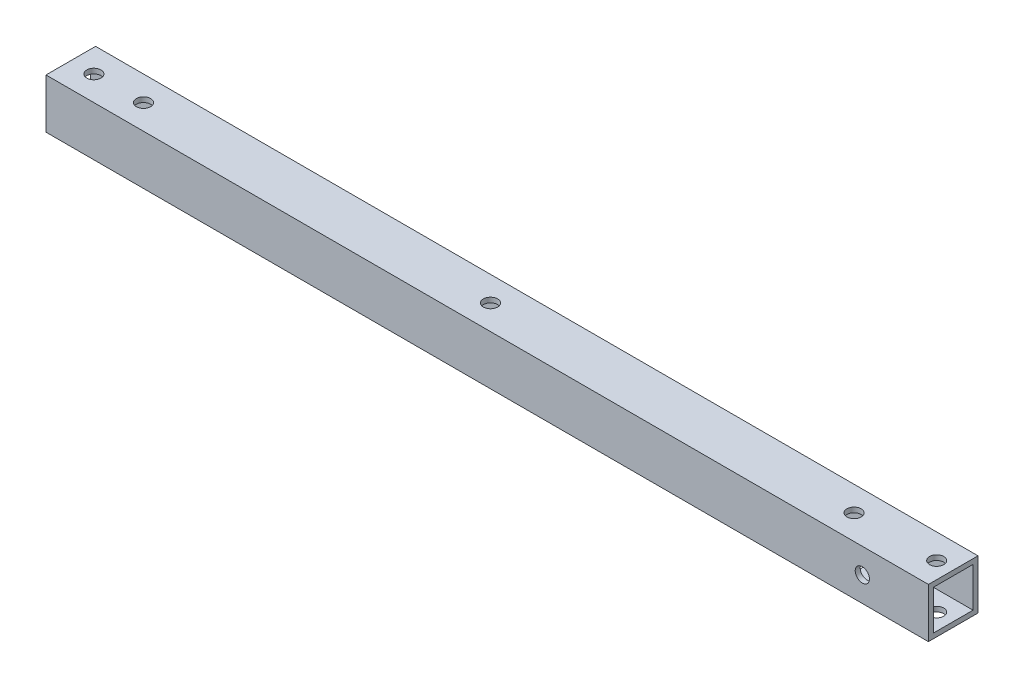
SolidWorks part; units mm, degrees
material "5052-H34"
ref_plane "正面" through (0, 0, 0) normal (0, 0, 1) x (1, 0, 0)
ref_plane "平面" through (0, 0, 0) normal (0, 1, 0) x (1, 0, 0)
ref_plane "右側面" through (0, 0, 0) normal (1, 0, 0) x (0, 0, -1)
sketch "ｽｹｯﾁ1" plane through (0, 0, 0) normal (1, 0, 0) x (0, 0, -1)
  line L1 (-7.5, 7.5) -> (7.5, 7.5)
  line L2 (-7.5, 7.5) -> (-7.5, -7.5)
  line L3 (-7.5, -7.5) -> (7.5, -7.5)
  line L4 (7.5, 7.5) -> (7.5, -7.5)
  line L5 (-7.5, 7.5) -> (7.5, -7.5) construction
  line L6 (-7.5, -7.5) -> (7.5, 7.5) construction
  point P0 (0, 0)
  dimension "D1" = 15
  dimension "D2" = 15
extrude "押し出し-薄板1" add sketch "ｽｹｯﾁ1" along normal blind 267 thin
sketch "ｽｹｯﾁ2" plane through (0, 7.5, 0) normal (0, 1, 0) x (1, 0, 0)
  line L0 (267, 0) -> (262, 0) construction
  line L1 (267, 7.5) -> (267, -7.5) construction
  line L2 (0, 0) -> (22, 0) construction
  line L6 (127, 0) -> (237, 0) construction
  circle A0 centre (262, 0) radius 2.15
  circle A1 centre (22, 0) radius 2.15
  circle A2 centre (7, 0) radius 2.15
  circle A3 centre (237, 0) radius 2.15
  circle A4 centre (127, 0) radius 2.15
  dimension "D1" = 4.3
  dimension "D3" = 4.3
  dimension "D6" = 4.3
  dimension "D2" = 5
  dimension "D4" = 7
  dimension "D5" = 22
  dimension "D7" = 110
  dimension "D8" = 30
extrude "ｶｯﾄ - 押し出し1" cut sketch "ｽｹｯﾁ2" against normal through all
sketch "ｽｹｯﾁ3" plane through (0, 0, 7.5) normal (0, 0, 1) x (1, 0, 0)
  line L0 (267, 0) -> (247, 0) construction
  line L1 (267, 7.5) -> (267, -7.5) construction
  circle A0 centre (247, 0) radius 2.15
  dimension "D1" = 4.3
  dimension "D2" = 20
extrude "ｶｯﾄ - 押し出し2" cut sketch "ｽｹｯﾁ3" against normal through all
